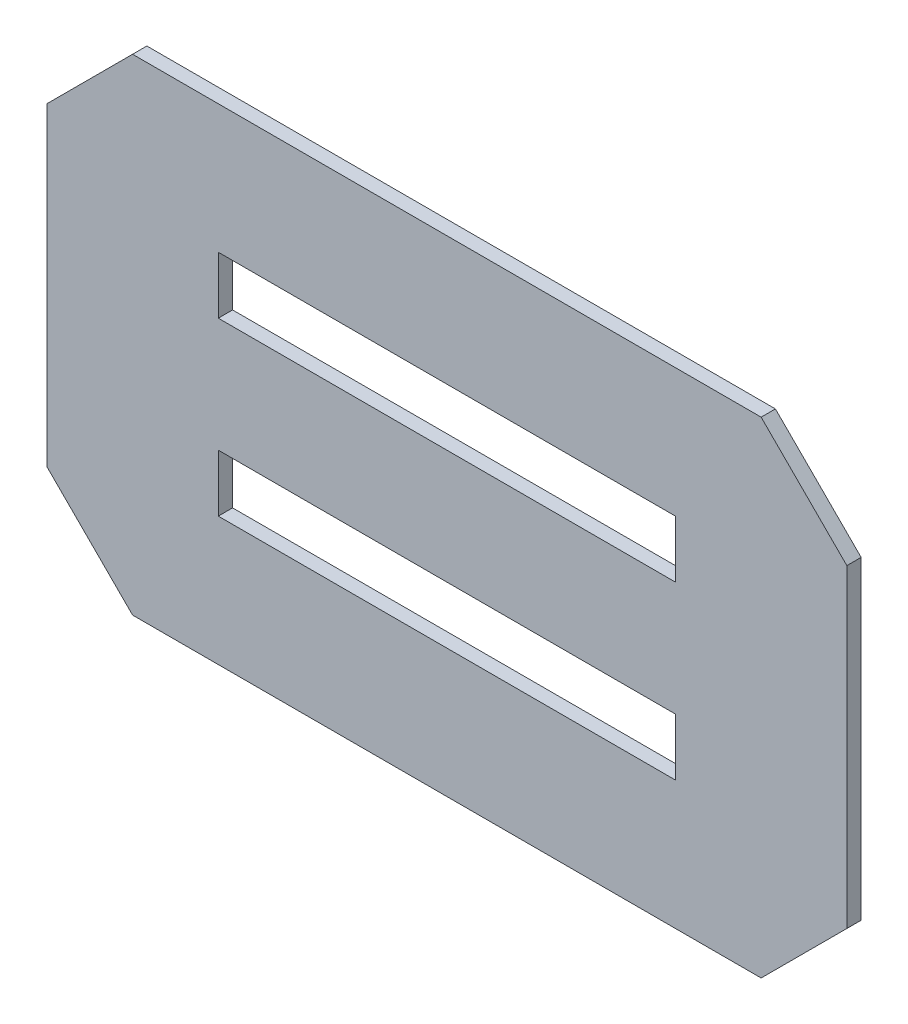
SolidWorks part; units mm, degrees
ref_plane "前视基准面" through (0, 0, 0) normal (0, 0, 1) x (1, 0, 0)
ref_plane "上视基准面" through (0, 0, 0) normal (0, 1, 0) x (1, 0, 0)
ref_plane "右视基准面" through (0, 0, 0) normal (1, 0, 0) x (0, 0, -1)
other "Configuration Table"
sketch "草图1" plane through (0, 0, 0) normal (0, 0, 1) x (1, 0, 0)
  line L0 (-14, 5.5) -> (-11, 8.5)
  line L1 (-11, 8.5) -> (11, 8.5)
  line L2 (-14, 5.5) -> (-14, -5.5)
  line L3 (-11, -8.5) -> (11, -8.5)
  line L4 (14, 5.5) -> (14, -5.5)
  line L5 (-14, 8.5) -> (14, -8.5) construction
  line L6 (-14, -8.5) -> (14, 8.5) construction
  line L7 (-14, -5.5) -> (-11, -8.5)
  line L8 (11, 8.5) -> (14, 5.5)
  line L9 (11, -8.5) -> (14, -5.5)
  line L10 (-1000, 0) -> (49000, 0) construction
  line L11 (-8, 4) -> (8, 4)
  line L12 (-8, 4) -> (-8, 2)
  line L13 (-8, 2) -> (8, 2)
  line L14 (8, 4) -> (8, 2)
  line L15 (-8, 4) -> (8, 2) construction
  line L16 (-8, 2) -> (8, 4) construction
  line L17 (-8, -2) -> (8, -2)
  line L18 (8, -4) -> (8, -2)
  line L19 (-8, -4) -> (8, -4)
  line L20 (-8, -4) -> (-8, -2)
  point P0 (0, 0)
  point P15 (0, 3)
  dimension "D1" = 28
  dimension "D2" = 17
  dimension "D3" = 16
  dimension "D4" = 2
  dimension "D5" = 3
extrude "凸台-拉伸1" add sketch "草图1" along normal blind 0.5
